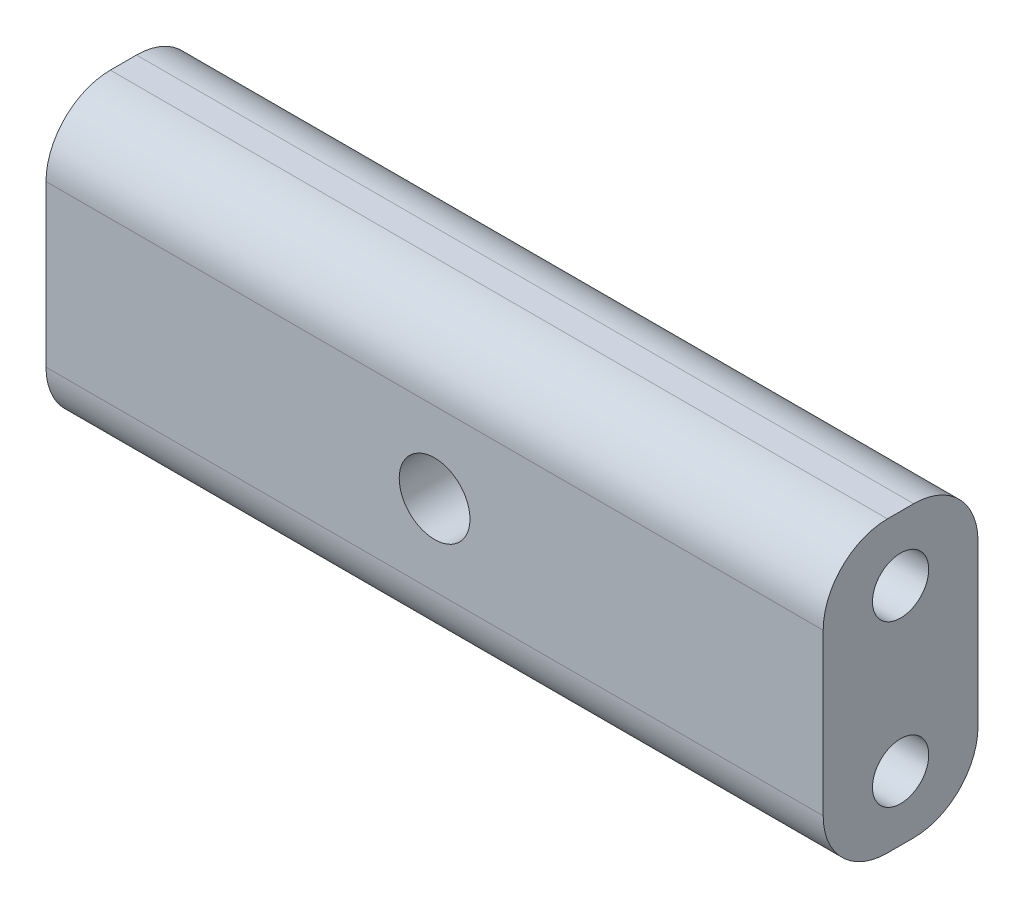
SolidWorks part; units mm, degrees
material "6061 Alloy"
ref_plane "Front Plane" through (0, 0, 0) normal (0, 0, 1) x (1, 0, 0)
ref_plane "Top Plane" through (0, 0, 0) normal (0, 1, 0) x (1, 0, 0)
ref_plane "Right Plane" through (0, 0, 0) normal (1, 0, 0) x (0, 0, -1)
sketch "Sketch1" plane through (0, 0, 0) normal (0, 0, 1) x (1, 0, 0)
  line L1 (-24.17, 9) -> (24.17, 9)
  line L2 (-24.17, 9) -> (-24.17, -9)
  line L3 (-24.17, -9) -> (24.17, -9)
  line L4 (24.17, 9) -> (24.17, -9)
  line L5 (0, -9) -> (0, 9) construction
  line L6 (-24.17, 0) -> (24.17, 0) construction
  point P0 (0, 0)
  dimension "D1" = 48.34
  dimension "D2" = 18
extrude "3/8" add sketch "Sketch1" along normal blind 9.63
sketch "Sketch2" plane through (-24.17, 0, 0) normal (-1, 0, 0) x (0, 0, 1)
  line L0 (4.815, 9) -> (4.815, -9) construction
  line L1 (9.63, 9) -> (0, 9) construction
  line L2 (9.63, -9) -> (0, -9) construction
  line L3 (0, 0) -> (9.63, 0) construction
  line L4 (9.63, 9) -> (9.63, -9) construction
  circle A0 centre (4.815, 5) radius 1.75
  circle A1 centre (4.815, -5) radius 1.75
  dimension "D2" = 3.5
  dimension "D1" = 5
extrude "M4_DRILL" cut sketch "Sketch2" against normal blind 8
sketch "Sketch3" plane through (24.17, 0, 0) normal (1, 0, 0) x (0, 0, -1)
  circle A0 centre (-4.815, -5) radius 1.75 construction
  circle A1 centre (-4.815, 5) radius 1.75 construction
  circle A2 centre (-4.815, -5) radius 1.75
  circle A3 centre (-4.815, 5) radius 1.75
extrude "M4_DRILL2" cut sketch "Sketch3" against normal blind 8
sketch "Sketch5" plane through (0, 0, 0) normal (0, 0, -1) x (-1, 0, 0)
  circle A0 centre (0, 0) radius 2.2
  dimension "D1" = 4.4
extrude "M5_DRILL" cut sketch "Sketch5" against normal up to surface (9.63 mm away) up to face at (0, 0, 9.63)
fillet "Fillet1" radius 4 4 edges at (0, -9, 9.63) (0, -9, 0) (0, 9, 9.63) (0, 9, 0)
